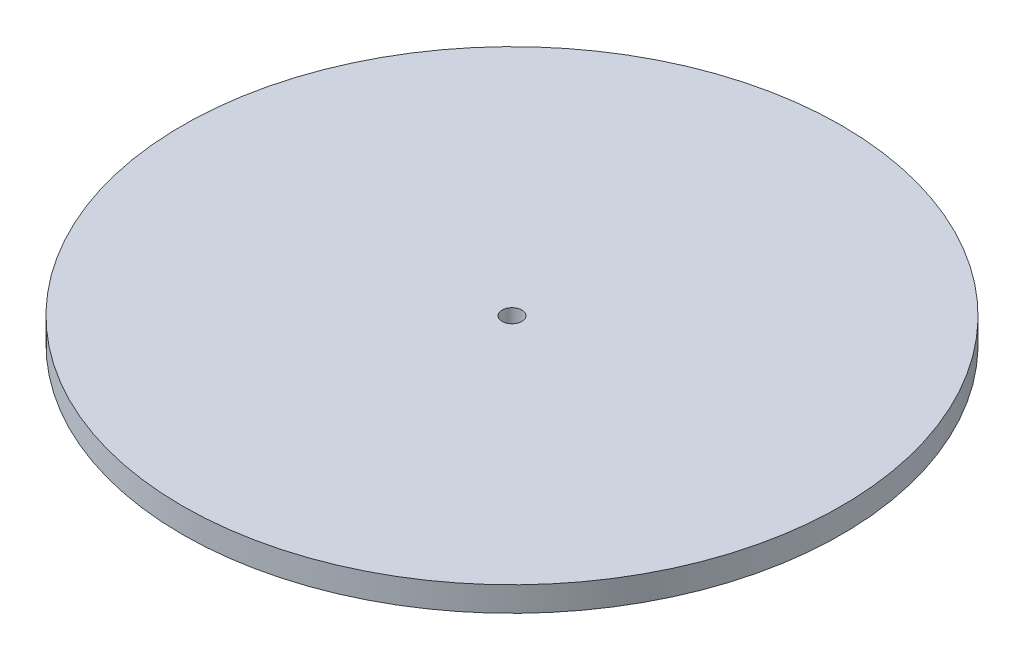
SolidWorks part; units mm, degrees
ref_plane "Front Plane" through (0, 0, 0) normal (0, 0, 1) x (1, 0, 0)
ref_plane "Top Plane" through (0, 0, 0) normal (0, 1, 0) x (1, 0, 0)
ref_plane "Right Plane" through (0, 0, 0) normal (1, 0, 0) x (0, 0, -1)
sketch "Sketch3" plane through (0, 0, 0) normal (0, 0, 1) x (1, 0, 0)
  line L0 (37, 8.51) -> (37, 12.51) construction
  line L1 (37, 12.51) -> (0, 12.51) construction
  line L2 (0, 12.51) -> (0, 0) construction
  line L4 (1.2, 12.51) -> (1.2, 7.51)
  line L5 (1.2, 7.51) -> (0, 7.51)
  line L6 (0, 7.51) -> (0, 0)
  line L7 (37, 8.51) -> (40, 8.51) construction
  line L8 (40, 8.51) -> (40, 12.51) construction
  line L9 (40, 12.51) -> (1.2, 12.51)
  line L10 (37, 8.51) -> (37, 9.51)
  line L11 (37, 9.51) -> (40, 9.51)
  line L12 (40, 9.51) -> (40, 12.51)
  spline S0 degree 8 poles (-3.7, 0.1351) (1.8414, -0.2575) (7.3828, -0.0656) (12.9242, 1.2483) (18.4656, 2.7546) (24.0071, 4.4206) (29.5485, 6.1675) (35.0899, 7.9076) (40.6313, 9.6526) knots 0 0 0 0 0 0 0 0 0 1 1 1 1 1 1 1 1 1 construction
  spline S1 degree 8 poles (0, 0) (4.625, 0.0012) (9.25, 0.5078) (13.875, 1.5615) (18.5, 2.8127) (23.125, 4.1777) (27.75, 5.6076) (32.375, 7.056) (37, 8.51) knots 0.083462 0.083462 0.083462 0.083462 0.083462 0.083462 0.083462 0.083462 0.083462 0.918087 0.918087 0.918087 0.918087 0.918087 0.918087 0.918087 0.918087 0.918087
  dimension "D1" = 3
  dimension "D2" = 1.2
  dimension "D3" = 5
  dimension "D4" = 3
  dimension "D5" = 40
  dimension "D6" = 8.51
  dimension "D7" = 37
  dimension "D8" = 4
revolve "Revolve4" add sketch "Sketch3" angle 360 about L2
sketch "Sketch5" plane through (0, 12.51, 0) normal (0, 1, 0) x (1, 0, 0)
  circle A0 centre (0, 0) radius 1.2
  circle A2 centre (0, 0) radius 1.2 construction
extrude "Cut-Extrude1" cut sketch "Sketch5" against normal through all
